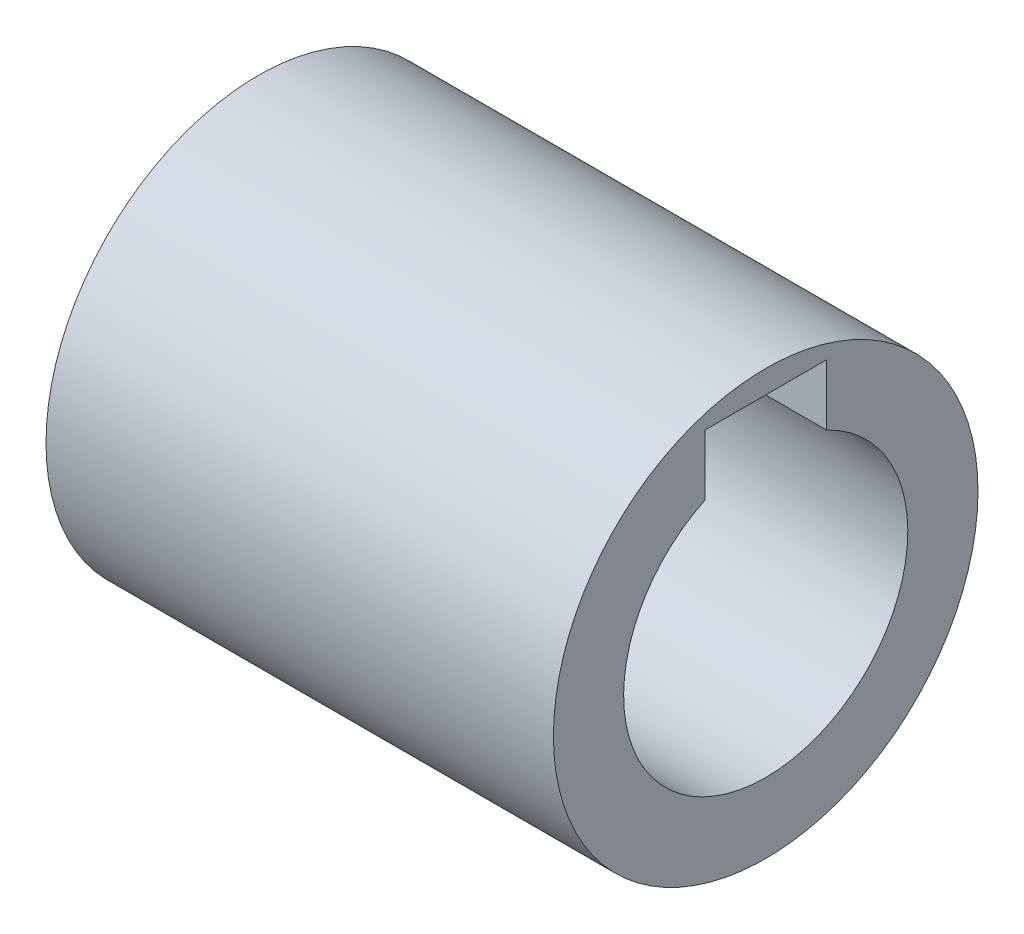
SolidWorks part; units mm, degrees
ref_plane "Plan de face" through (0, 0, 0) normal (0, 0, 1) x (1, 0, 0)
ref_plane "Plan de dessus" through (0, 0, 0) normal (0, 1, 0) x (1, 0, 0)
ref_plane "Plan de droite" through (0, 0, 0) normal (1, 0, 0) x (0, 0, -1)
sketch "Esquisse1" plane through (0, 0, 0) normal (1, 0, 0) x (0, 0, -1)
  line L0 (0, 0) -> (0, 1.7233) construction
  line L5 (-1.5, 4.6623) -> (1.5, 4.6623)
  line L10 (-1.5, 4.6623) -> (-1.5, 3.1623)
  line L11 (-1.5, 3.1623) -> (1.5, 3.1623) construction
  line L12 (1.5, 4.6623) -> (1.5, 3.1623)
  circle A1 centre (0, 0) radius 3.5 construction
  arc A4 (1.5, 3.1623) -> (-1.5, 3.1623) centre (0, 0) cw
  circle A5 centre (0, 0) radius 5.2293
  dimension "D1" = 7
  dimension "D2" = 3
  dimension "D3" = 1.5
extrude "Boss.-Extru.1" add sketch "Esquisse1" along normal blind 12.5 contours A5 L12 A4 L10 L5
